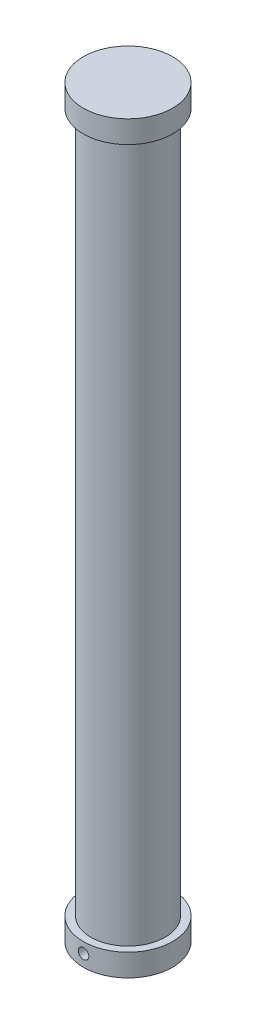
SolidWorks part; units mm, degrees
ref_plane "Front Plane" through (0, 0, 0) normal (0, 0, 1) x (1, 0, 0)
ref_plane "Top Plane" through (0, 0, 0) normal (0, 1, 0) x (1, 0, 0)
ref_plane "Right Plane" through (0, 0, 0) normal (1, 0, 0) x (0, 0, -1)
sketch "Sketch1" plane through (0, 0, 0) normal (0, 0, 1) x (1, 0, 0)
  line L0 (0, 0) -> (3, 0)
  line L1 (3, 0) -> (3, 1.5)
  line L2 (3, 1.5) -> (2.5, 1.5)
  line L3 (2.5, 1.5) -> (2.5, 48.5)
  line L4 (2.5, 48.5) -> (3, 48.5)
  line L5 (3, 48.5) -> (3, 50)
  line L6 (3, 50) -> (0, 50)
  line L7 (0, 50) -> (0, 0)
  point P3 (3, 49.25)
  dimension "D1" = 1.5
  dimension "D2" = 50
  dimension "D3" = 2.5
  dimension "D4" = 3
revolve "Revolve1" add sketch "Sketch1" angle 360 about L7
sketch "Sketch2" plane through (0, 0, 0) normal (0, 0, 1) x (1, 0, 0)
  circle A0 centre (0, 0.8029) radius 0.35
  dimension "D1" = 0.7
extrude "Cut-Extrude1" cut sketch "Sketch2" along normal mid plane 10
